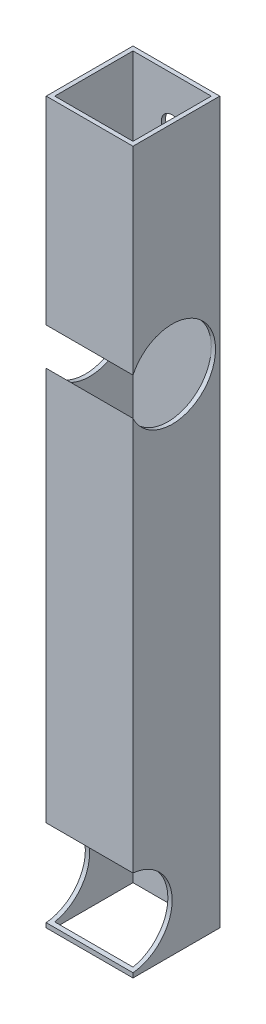
SolidWorks part; units mm, degrees
ref_plane "Front Plane" through (0, 0, 0) normal (0, 0, 1) x (1, 0, 0)
ref_plane "Top Plane" through (0, 0, 0) normal (0, 1, 0) x (1, 0, 0)
ref_plane "Right Plane" through (0, 0, 0) normal (1, 0, 0) x (0, 0, -1)
sketch "Sketch1" plane through (0, 0, 0) normal (0, 1, 0) x (1, 0, 0)
  line L1 (-11.4554, -11.4554) -> (11.4554, -11.4554)
  line L2 (-11.4554, -11.4554) -> (-11.4554, 11.4554)
  line L3 (-11.4554, 11.4554) -> (11.4554, 11.4554)
  line L4 (11.4554, -11.4554) -> (11.4554, 11.4554)
  line L5 (-11.4554, -11.4554) -> (11.4554, 11.4554) construction
  line L6 (-11.4554, 11.4554) -> (11.4554, -11.4554) construction
  line L7 (-12.7, -12.7) -> (12.7, -12.7)
  line L8 (-12.7, -12.7) -> (-12.7, 12.7)
  line L9 (-12.7, 12.7) -> (12.7, 12.7)
  line L10 (12.7, -12.7) -> (12.7, 12.7)
  line L11 (-12.7, -12.7) -> (12.7, 12.7) construction
  line L12 (-12.7, 12.7) -> (12.7, -12.7) construction
  point P0 (0, 0)
  point P6 (0, 0)
  dimension "D1" = 25.4
  dimension "D2" = 25.4
  dimension "D3" = 1.2446
  dimension "D4" = 1.2446
extrude "Boss-Extrude1" add sketch "Sketch1" along normal blind 210.82
sketch "Sketch2" plane through (12.7, 0, 0) normal (1, 0, 0) x (0, 0, -1)
  line L2 (12.7, 210.82) -> (12.7, 0) construction
  line L3 (-12.7, 210.82) -> (12.7, 210.82) construction
  circle A0 centre (-1.2446, 147.32) radius 12.7
  circle A1 centre (-13.9446, 13.97) radius 12.7
  dimension "D1" = 25.4
  dimension "D2" = 25.4
  dimension "D3" = 1.2446
  dimension "D4" = 133.35
  dimension "D5" = 63.5
  dimension "D6" = 12.7
extrude "Cut-Extrude1" cut sketch "Sketch2" against normal blind 210.82 contours A1 | A0
sketch "Sketch3" plane through (0, 0, -12.7) normal (0, 0, -1) x (-1, 0, 0)
  line L2 (-12.7, 210.82) -> (12.7, 210.82) construction
  circle A0 centre (0, 197.1675) radius 3.175
  circle A1 centre (0, 14.2875) radius 3.175
  point P9 (0, 0)
  dimension "D1" = 10.4775
  dimension "D2" = 6.35
  dimension "D3" = 6.35
  dimension "D4" = 182.88
extrude "Cut-Extrude2" cut sketch "Sketch3" against normal up to surface (1.2446 mm away) up to face at (0, 119.38, -11.4554)
